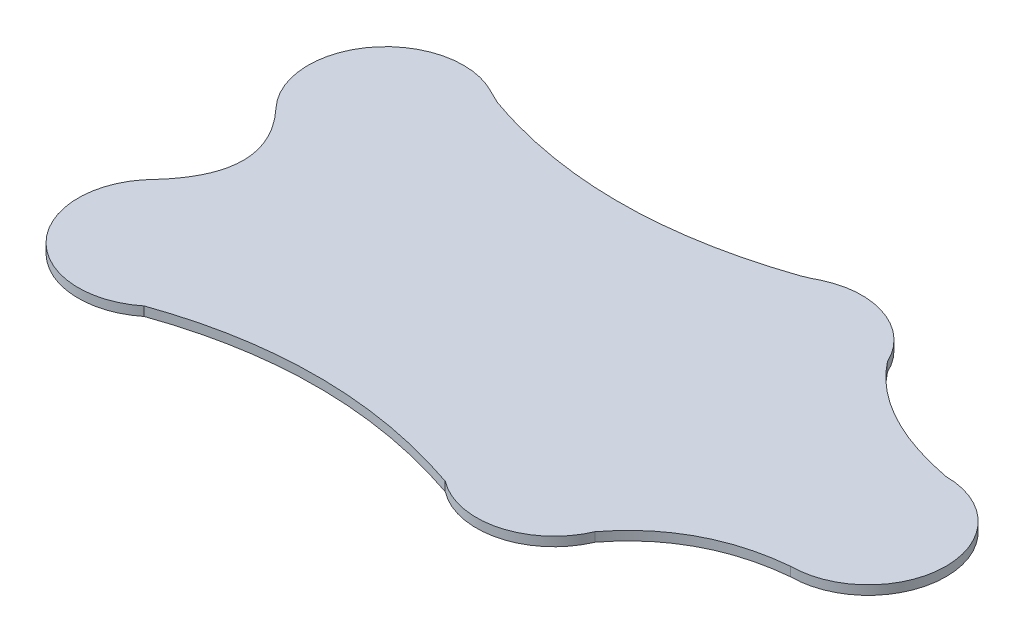
SolidWorks part; units mm, degrees
ref_plane "Front Plane" through (0, 0, 0) normal (0, 0, 1) x (1, 0, 0)
ref_plane "Top Plane" through (0, 0, 0) normal (0, 1, 0) x (1, 0, 0)
ref_plane "Right Plane" through (0, 0, 0) normal (1, 0, 0) x (0, 0, -1)
sketch "Sketch2" plane through (0, 0, 0) normal (0, 1, 0) x (1, 0, 0)
  line L3 (-81.404, 17.6381) -> (-75.1584, 11.0025) construction
  line L4 (-75.1584, 11.0025) -> (-81.27, 4.2788) construction
  line L5 (-69.8762, -8.3007) -> (-53.7895, -2.6134) construction
  line L6 (-53.7895, -2.6134) -> (-36.8162, -8.4386) construction
  line L7 (-23.8356, -5.0227) -> (-18.7887, 1.5516) construction
  line L8 (-18.7887, 1.5516) -> (-9.8729, 2.3889) construction
  line L9 (-53.7895, -2.6134) -> (-53.7895, -5.4911) construction
  line L11 (-69.8762, 30.3057) -> (-70.6533, 30.6899) construction
  line L12 (-23.953, 27.063) -> (-19.3557, 21.2033) construction
  line L13 (-19.3557, 21.2033) -> (-9.8729, 19.3889) construction
  line L14 (-69.8762, 30.3057) -> (-53.7895, 24.6183) construction
  line L15 (-53.7895, 24.6183) -> (-36.8162, 30.4436) construction
  line L16 (-70.6533, 30.6899) -> (-71.1829, 30.9469) construction
  arc A7 (-71.1829, 30.9469) -> (-81.404, 17.6381) centre (-75.2145, 23.4639) ccw
  arc A8 (-81.27, 4.2788) -> (-69.8762, -8.3007) centre (-75.2145, -1.6861) ccw
  arc A10 (-36.8162, -8.4386) -> (-23.8356, -5.0227) centre (-31.6534, -1.6861) ccw
  arc A11 (-23.953, 27.063) -> (-35.2696, 31.1563) centre (-31.6534, 23.4639) ccw
  arc A12 (-9.8729, 2.3889) -> (-9.8729, 19.3889) centre (-9.8729, 10.8889) ccw
  spline S0 degree 2 poles (-81.404, 17.6381) (-75.1584, 11.0025) (-81.27, 4.2788) knots 0 0 0 1 1 1
  spline S1 degree 2 poles (-69.8762, -8.3007) (-53.7895, -2.6134) (-36.8162, -8.4386) knots 0 0 0 1 1 1
  spline S2 degree 2 poles (-23.8356, -5.0227) (-18.7887, 1.5516) (-9.8729, 2.3889) knots 0 0 0 1 1 1
  spline S4 degree 2 poles (-23.953, 27.063) (-19.3557, 21.2033) (-9.8729, 19.3889) knots 0 0 0 1 1 1
  spline S5 degree 2 poles (-69.8762, 30.3057) (-53.7895, 24.6183) (-36.8162, 30.4436) knots 0 0 0 1 1 1
  spline S6 degree 2 poles (-36.8162, 30.4436) (-36.0219, 30.7556) (-35.2696, 31.1563) knots 0 0 0 1 1 1
  spline S7 degree 2 poles (-69.8762, 30.3057) (-70.6533, 30.6899) (-71.1829, 30.9469) knots 0 0 0 1 1 1
  dimension "D15" = 17
  dimension "D16" = 17
  dimension "D18" = 17
  dimension "D19" = 17
  dimension "D20" = 17
extrude "Boss-Extrude1" add sketch "Sketch2" along normal blind 1
